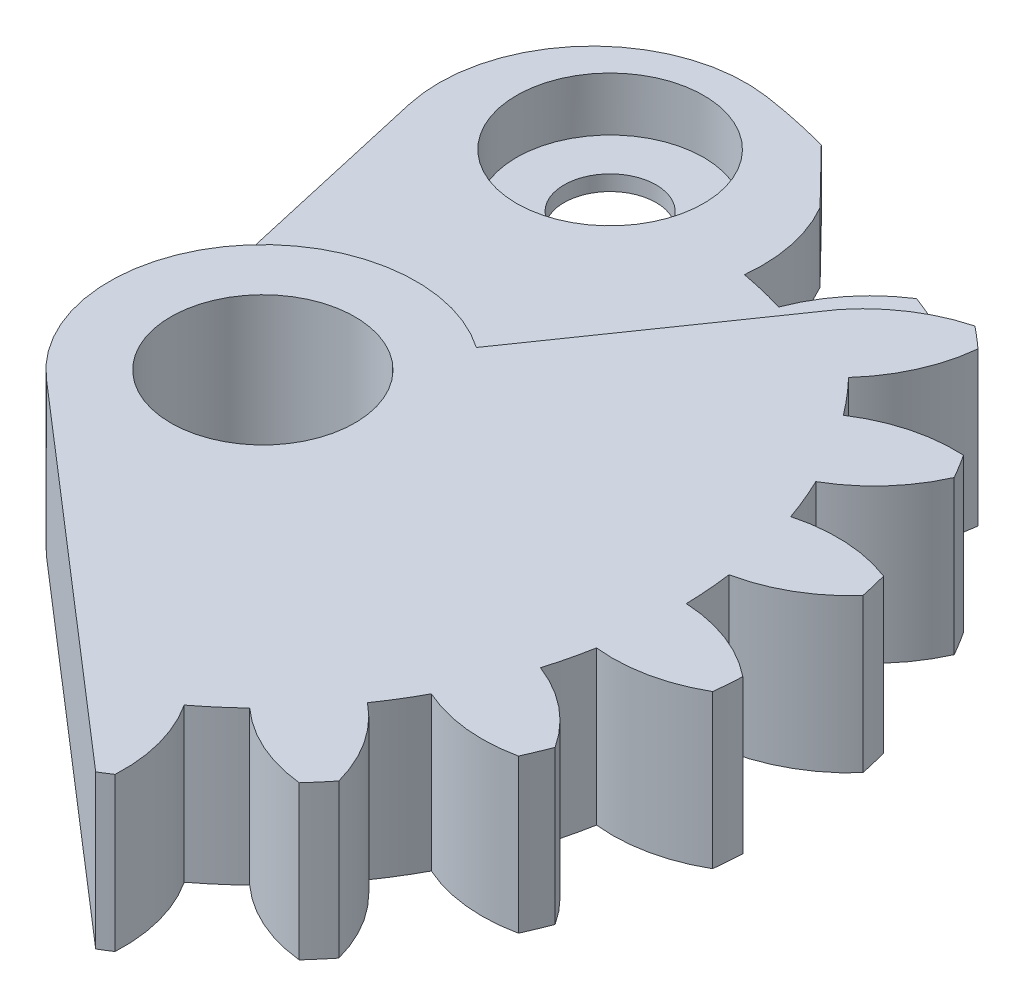
SolidWorks part; units mm, degrees
ref_plane "前视基准面" through (0, 0, 0) normal (0, 0, 1) x (1, 0, 0)
ref_plane "上视基准面" through (0, 0, 0) normal (0, 1, 0) x (1, 0, 0)
ref_plane "右视基准面" through (0, 0, 0) normal (1, 0, 0) x (0, 0, -1)
other "Configuration Table"
sketch "草图1" plane through (0, 0, 0) normal (0, 1, 0) x (1, 0, 0)
  line L0 (0, 0) -> (0, 56.9379) construction
  line L1 (0, 0) -> (19.4661, 53.4826) construction
  line L2 (0, 0) -> (4.4104, 56.0389) construction
  line L3 (0, 30) -> (9.6418, 26.4907) construction
  circle A0 centre (0, 0) radius 30 construction
  circle A1 centre (0, 0) radius 27
  circle A2 centre (0, 0) radius 33
  arc A3 (1.6756, 32.9574) -> (-0.6065, 26.9932) centre (9.6418, 26.4907) ccw
  arc A4 (3.5007, 32.8138) -> (4.8217, 26.566) centre (-5.3791, 27.6728) cw
  dimension "D1" = 60
  dimension "D2" = 3
  dimension "D3" = 3
  dimension "D4" = 20
  dimension "D5" = 4.5
extrude "凸台-拉伸2" add sketch "草图1" along normal blind 10 contours A1
sketch "草图3" plane through (0, 10, 0) normal (0, 1, 0) x (1, 0, 0)
  arc A0 (4.8217, 26.566) -> (3.5007, 32.8138) centre (-5.3791, 27.6728) ccw construction
  circle A1 centre (0, 0) radius 33
  circle A2 centre (0, 0) radius 33
  circle A3 centre (0, 0) radius 27
  circle A4 centre (0, 0) radius 27
  arc A5 (1.6756, 32.9574) -> (-0.6065, 26.9932) centre (9.6418, 26.4907) ccw construction
  arc A6 (4.8217, 26.566) -> (3.5007, 32.8138) centre (-5.3791, 27.6728) ccw
  arc A7 (1.6756, 32.9574) -> (-0.6065, 26.9932) centre (9.6418, 26.4907) ccw
  arc A8 (12.795, 23.7758) -> (13.4694, 30.126) centre (3.4356, 27.9806) ccw
  arc A9 (11.778, 30.8266) -> (7.7646, 25.8595) centre (17.356, 22.2146) ccw
  arc A10 (19.5159, 18.6582) -> (22.1196, 24.4892) centre (11.9139, 25.5495) ccw
  arc A11 (20.7275, 25.6782) -> (15.3755, 22.1944) centre (23.3712, 15.7641) ccw
  arc A12 (24.3264, 11.7143) -> (28.6046, 16.4553) centre (19.2261, 20.6174) ccw
  arc A13 (27.648, 18.0163) -> (21.4815, 16.3568) centre (27.0987, 7.7704) ccw
  arc A14 (26.7557, 3.6237) -> (32.2896, 6.8106) centre (24.6562, 13.6672) ccw
  arc A15 (31.8622, 8.5908) -> (25.4846, 8.9181) centre (28.1736, -0.9838) ccw
  arc A16 (26.566, -4.8217) -> (32.8138, -3.5007) centre (27.6728, 5.3791) ccw
  arc A17 (32.9574, -1.6756) -> (26.9932, 0.6065) centre (26.4907, -9.6418) ccw
  arc A18 (23.7758, -12.795) -> (30.126, -13.4694) centre (27.9806, -3.4356) ccw
  arc A19 (30.8266, -11.778) -> (25.8595, -7.7646) centre (22.2146, -17.356) ccw
  arc A20 (18.6582, -19.5159) -> (24.4892, -22.1196) centre (25.5495, -11.9139) ccw
  arc A21 (25.6782, -20.7275) -> (22.1944, -15.3755) centre (15.7641, -23.3712) ccw
  arc A22 (11.7143, -24.3264) -> (16.4553, -28.6046) centre (20.6174, -19.2261) ccw
  arc A23 (18.0163, -27.648) -> (16.3568, -21.4815) centre (7.7704, -27.0987) ccw
  arc A24 (3.6237, -26.7557) -> (6.8106, -32.2896) centre (13.6672, -24.6562) ccw
  arc A25 (8.5908, -31.8622) -> (8.9181, -25.4846) centre (-0.9838, -28.1736) ccw
  arc A26 (-4.8217, -26.566) -> (-3.5007, -32.8138) centre (5.3791, -27.6728) ccw
  arc A27 (-1.6756, -32.9574) -> (0.6065, -26.9932) centre (-9.6418, -26.4907) ccw
  arc A28 (-12.795, -23.7758) -> (-13.4694, -30.126) centre (-3.4356, -27.9806) ccw
  arc A29 (-11.778, -30.8266) -> (-7.7646, -25.8595) centre (-17.356, -22.2146) ccw
  arc A30 (-19.5159, -18.6582) -> (-22.1196, -24.4892) centre (-11.9139, -25.5495) ccw
  arc A31 (-20.7275, -25.6782) -> (-15.3755, -22.1944) centre (-23.3712, -15.7641) ccw
  arc A32 (-24.3264, -11.7143) -> (-28.6046, -16.4553) centre (-19.2261, -20.6174) ccw
  arc A33 (-27.648, -18.0163) -> (-21.4815, -16.3568) centre (-27.0987, -7.7704) ccw
  arc A34 (-26.7557, -3.6237) -> (-32.2896, -6.8106) centre (-24.6562, -13.6672) ccw
  arc A35 (-31.8622, -8.5908) -> (-25.4846, -8.9181) centre (-28.1736, 0.9838) ccw
  arc A36 (-26.566, 4.8217) -> (-32.8138, 3.5007) centre (-27.6728, -5.3791) ccw
  arc A37 (-32.9574, 1.6756) -> (-26.9932, -0.6065) centre (-26.4907, 9.6418) ccw
  arc A38 (-23.7758, 12.795) -> (-30.126, 13.4694) centre (-27.9806, 3.4356) ccw
  arc A39 (-30.8266, 11.778) -> (-25.8595, 7.7646) centre (-22.2146, 17.356) ccw
  arc A40 (-18.6582, 19.5159) -> (-24.4892, 22.1196) centre (-25.5495, 11.9139) ccw
  arc A41 (-25.6782, 20.7275) -> (-22.1944, 15.3755) centre (-15.7641, 23.3712) ccw
  arc A42 (-11.7143, 24.3264) -> (-16.4553, 28.6046) centre (-20.6174, 19.2261) ccw
  arc A43 (-18.0163, 27.648) -> (-16.3568, 21.4815) centre (-7.7704, 27.0987) ccw
  arc A44 (-3.6237, 26.7557) -> (-6.8106, 32.2896) centre (-13.6672, 24.6562) ccw
  arc A45 (-8.5908, 31.8622) -> (-8.9181, 25.4846) centre (0.9838, 28.1736) ccw
  point P129 (0, 0)
  circle M3 centre (0, 0) radius 27
  dimension "D1" = 0
  dimension "D2" = 0
  dimension "D3" = 20
extrude "凸台-拉伸3" add sketch "草图3" against normal blind 10 contours A2 A45 A44 M3 | A2 A43 A42 M3 | A2 A41 A40 M3 | A2 A39 A38 M3 | A2 A37 A36 M3 | A2 A35 A34 M3 | A2 A33 A32 M3 | A2 A31 A30 M3 | A2 A29 A28 M3 | A2 A27 A26 M3 | A2 A25 A24 M3 | A2 A23 A22 M3 | A2 A21 A20 M3 | A2 A19 A18 M3 | A2 A17 A16 M3 | A2 A15 A14 M3 | A2 A13 A12 M3 | A2 A11 A10 M3 | A2 A9 A8 M3 | A2 A7 A6 M3
sketch "草图4" plane through (0, 10, 0) normal (0, 1, 0) x (1, 0, 0)
  line L0 (0, 0) -> (23.0213, -14.1075)
  line L1 (0, 0) -> (-2.1184, 26.9168)
  line L2 (-9.5508, 2.9635) -> (19.9356, 97.9927)
  line L5 (-6.5422, -7.5631) -> (68.7094, -72.6568)
  arc A0 (16.4553, -28.6046) -> (18.0163, -27.648) centre (0, 0) ccw construction
  arc A1 (-0.6065, 26.9932) -> (-3.6237, 26.7557) centre (0, 0) ccw construction
  circle A2 centre (0, 0) radius 100
  arc A3 (22.1944, -15.3755) -> (23.7758, -12.795) centre (0, 0) ccw construction
  circle A4 centre (0, 0) radius 10
  point P9 (17.2425, -28.1371)
  point P18 (-2.1184, 26.9168)
  dimension "D1" = 20
  dimension "D2" = 200
extrude "切除-拉伸2" cut sketch "草图4" against normal through all
sketch "草图6" plane through (0, 10, 0) normal (0, 1, 0) x (1, 0, 0)
  line L2 (-6.5422, -7.5631) -> (17.2425, -28.1371)
  line L3 (-2.1184, 26.9168) -> (-9.5508, 2.9635)
  line L4 (-6.5422, -7.5631) -> (17.2425, -28.1371)
  line L5 (-2.1184, 26.9168) -> (-9.5508, 2.9635)
  circle A0 centre (0, 0) radius 6
  arc A22 (-9.5508, 2.9635) -> (-6.5422, -7.5631) centre (0, 0) ccw
  arc A23 (17.2425, -28.1371) -> (18.0163, -27.648) centre (0, 0) ccw
  arc A24 (30.8266, -11.778) -> (25.8595, -7.7646) centre (22.2146, -17.356) ccw
  arc A25 (25.8595, -7.7646) -> (26.566, -4.8217) centre (0, 0) ccw
  arc A26 (26.566, -4.8217) -> (32.8138, -3.5007) centre (27.6728, 5.3791) ccw
  arc A27 (32.8138, -3.5007) -> (32.9574, -1.6756) centre (0, 0) ccw
  arc A28 (32.9574, -1.6756) -> (26.9932, 0.6065) centre (26.4907, -9.6418) ccw
  arc A29 (26.9932, 0.6065) -> (26.7557, 3.6237) centre (0, 0) ccw
  arc A30 (26.7557, 3.6237) -> (32.2896, 6.8106) centre (24.6562, 13.6672) ccw
  arc A31 (32.2896, 6.8106) -> (31.8622, 8.5908) centre (0, 0) ccw
  arc A32 (31.8622, 8.5908) -> (25.4846, 8.9181) centre (28.1736, -0.9838) ccw
  arc A33 (25.4846, 8.9181) -> (24.3264, 11.7143) centre (0, 0) ccw
  arc A34 (24.3264, 11.7143) -> (28.6046, 16.4553) centre (19.2261, 20.6174) ccw
  arc A35 (28.6046, 16.4553) -> (27.648, 18.0163) centre (0, 0) ccw
  arc A36 (27.648, 18.0163) -> (21.4815, 16.3568) centre (27.0987, 7.7704) ccw
  arc A37 (21.4815, 16.3568) -> (19.5159, 18.6582) centre (0, 0) ccw
  arc A38 (19.5159, 18.6582) -> (22.1196, 24.4892) centre (11.9139, 25.5495) ccw
  arc A39 (22.1196, 24.4892) -> (20.7275, 25.6782) centre (0, 0) ccw
  arc A40 (20.7275, 25.6782) -> (15.3755, 22.1944) centre (23.3712, 15.7641) ccw
  arc A41 (15.3755, 22.1944) -> (12.795, 23.7758) centre (0, 0) ccw
  arc A42 (12.795, 23.7758) -> (13.4694, 30.126) centre (3.4356, 27.9806) ccw
  arc A43 (13.4694, 30.126) -> (11.778, 30.8266) centre (0, 0) ccw
  arc A44 (-9.5508, 2.9635) -> (-6.5422, -7.5631) centre (0, 0) ccw
  arc A45 (17.2425, -28.1371) -> (18.0163, -27.648) centre (0, 0) ccw
  arc A46 (30.8266, -11.778) -> (25.8595, -7.7646) centre (22.2146, -17.356) ccw
  arc A47 (25.8595, -7.7646) -> (26.566, -4.8217) centre (0, 0) ccw
  arc A48 (26.566, -4.8217) -> (32.8138, -3.5007) centre (27.6728, 5.3791) ccw
  arc A49 (32.8138, -3.5007) -> (32.9574, -1.6756) centre (0, 0) ccw
  arc A50 (32.9574, -1.6756) -> (26.9932, 0.6065) centre (26.4907, -9.6418) ccw
  arc A51 (26.9932, 0.6065) -> (26.7557, 3.6237) centre (0, 0) ccw
  arc A52 (26.7557, 3.6237) -> (32.2896, 6.8106) centre (24.6562, 13.6672) ccw
  arc A53 (32.2896, 6.8106) -> (31.8622, 8.5908) centre (0, 0) ccw
  arc A54 (31.8622, 8.5908) -> (25.4846, 8.9181) centre (28.1736, -0.9838) ccw
  arc A55 (25.4846, 8.9181) -> (24.3264, 11.7143) centre (0, 0) ccw
  arc A56 (24.3264, 11.7143) -> (28.6046, 16.4553) centre (19.2261, 20.6174) ccw
  arc A57 (28.6046, 16.4553) -> (27.648, 18.0163) centre (0, 0) ccw
  arc A58 (27.648, 18.0163) -> (21.4815, 16.3568) centre (27.0987, 7.7704) ccw
  arc A59 (21.4815, 16.3568) -> (19.5159, 18.6582) centre (0, 0) ccw
  arc A60 (19.5159, 18.6582) -> (22.1196, 24.4892) centre (11.9139, 25.5495) ccw
  arc A61 (22.1196, 24.4892) -> (20.7275, 25.6782) centre (0, 0) ccw
  arc A62 (20.7275, 25.6782) -> (15.3755, 22.1944) centre (23.3712, 15.7641) ccw
  arc A63 (15.3755, 22.1944) -> (12.795, 23.7758) centre (0, 0) ccw
  arc A64 (12.795, 23.7758) -> (13.4694, 30.126) centre (3.4356, 27.9806) ccw
  arc A65 (13.4694, 30.126) -> (11.778, 30.8266) centre (0, 0) ccw
  arc A73 (11.778, 30.8266) -> (7.7646, 25.8595) centre (17.356, 22.2146) ccw
  arc A74 (11.778, 30.8266) -> (7.7646, 25.8595) centre (17.356, 22.2146) ccw
  arc A75 (7.7646, 25.8595) -> (4.8217, 26.566) centre (0, 0) ccw
  arc A76 (7.7646, 25.8595) -> (4.8217, 26.566) centre (0, 0) ccw
  arc A77 (4.8217, 26.566) -> (3.5007, 32.8138) centre (-5.3791, 27.6728) ccw
  arc A78 (4.8217, 26.566) -> (3.5007, 32.8138) centre (-5.3791, 27.6728) ccw
  arc A79 (3.5007, 32.8138) -> (1.6756, 32.9574) centre (0, 0) ccw
  arc A80 (3.5007, 32.8138) -> (1.6756, 32.9574) centre (0, 0) ccw
  arc A81 (1.6756, 32.9574) -> (-0.6065, 26.9932) centre (9.6418, 26.4907) ccw
  arc A82 (1.6756, 32.9574) -> (-0.6065, 26.9932) centre (9.6418, 26.4907) ccw
  arc A83 (-0.6065, 26.9932) -> (-2.1184, 26.9168) centre (0, 0) ccw
  arc A84 (-0.6065, 26.9932) -> (-2.1184, 26.9168) centre (0, 0) ccw
  arc A89 (25.6782, -20.7275) -> (22.1944, -15.3755) centre (15.7641, -23.3712) ccw
  arc A90 (25.6782, -20.7275) -> (22.1944, -15.3755) centre (15.7641, -23.3712) ccw
  arc A91 (22.1944, -15.3755) -> (23.7758, -12.795) centre (0, 0) ccw
  arc A92 (22.1944, -15.3755) -> (23.7758, -12.795) centre (0, 0) ccw
  arc A93 (23.7758, -12.795) -> (30.126, -13.4694) centre (27.9806, -3.4356) ccw
  arc A94 (23.7758, -12.795) -> (30.126, -13.4694) centre (27.9806, -3.4356) ccw
  arc A95 (30.126, -13.4694) -> (30.8266, -11.778) centre (0, 0) ccw
  arc A96 (30.126, -13.4694) -> (30.8266, -11.778) centre (0, 0) ccw
  arc A101 (18.0163, -27.648) -> (16.3568, -21.4815) centre (7.7704, -27.0987) ccw
  arc A102 (18.0163, -27.648) -> (16.3568, -21.4815) centre (7.7704, -27.0987) ccw
  arc A103 (16.3568, -21.4815) -> (18.6582, -19.5159) centre (0, 0) ccw
  arc A104 (16.3568, -21.4815) -> (18.6582, -19.5159) centre (0, 0) ccw
  arc A105 (18.6582, -19.5159) -> (24.4892, -22.1196) centre (25.5495, -11.9139) ccw
  arc A106 (18.6582, -19.5159) -> (24.4892, -22.1196) centre (25.5495, -11.9139) ccw
  arc A107 (24.4892, -22.1196) -> (25.6782, -20.7275) centre (0, 0) ccw
  arc A108 (24.4892, -22.1196) -> (25.6782, -20.7275) centre (0, 0) ccw
  dimension "D2" = 12
  dimension "D1" = 0
extrude "切除-拉伸3" cut sketch "草图6" against normal blind 10 contours A0
sketch "草图9" plane through (0, 10, 0) normal (0, 1, 0) x (1, 0, 0)
  line L0 (-10, 0) -> (-18.3373, 36.811)
  line L1 (-6.5422, -7.5631) -> (4.8217, 26.566)
  line L2 (4.8217, 26.566) -> (7.168, 33.6128)
  line L3 (-6.5422, -7.5631) -> (17.2425, -28.1371)
  line L4 (-2.1184, 26.9168) -> (-9.5508, 2.9635)
  line L5 (-6.5422, -7.5631) -> (17.2425, -28.1371)
  line L6 (-2.1184, 26.9168) -> (-9.5508, 2.9635)
  arc A0 (-9.5508, 2.9635) -> (-6.5422, -7.5631) centre (0, 0) ccw construction
  circle A1 centre (-10, 0) radius 37.7433
  arc A42 (-9.5508, 2.9635) -> (-6.5422, -7.5631) centre (0, 0) ccw
  arc A43 (17.2425, -28.1371) -> (18.0163, -27.648) centre (0, 0) ccw
  arc A48 (18.0163, -27.648) -> (16.3568, -21.4815) centre (7.7704, -27.0987) ccw
  arc A49 (16.3568, -21.4815) -> (18.6582, -19.5159) centre (0, 0) ccw
  arc A50 (18.6582, -19.5159) -> (24.4892, -22.1196) centre (25.5495, -11.9139) ccw
  arc A51 (24.4892, -22.1196) -> (25.6782, -20.7275) centre (0, 0) ccw
  arc A52 (25.6782, -20.7275) -> (22.1944, -15.3755) centre (15.7641, -23.3712) ccw
  arc A53 (22.1944, -15.3755) -> (23.7758, -12.795) centre (0, 0) ccw
  arc A54 (23.7758, -12.795) -> (30.126, -13.4694) centre (27.9806, -3.4356) ccw
  arc A55 (30.126, -13.4694) -> (30.8266, -11.778) centre (0, 0) ccw
  arc A56 (30.8266, -11.778) -> (25.8595, -7.7646) centre (22.2146, -17.356) ccw
  arc A57 (25.8595, -7.7646) -> (26.566, -4.8217) centre (0, 0) ccw
  arc A58 (26.566, -4.8217) -> (32.8138, -3.5007) centre (27.6728, 5.3791) ccw
  arc A59 (32.8138, -3.5007) -> (32.9574, -1.6756) centre (0, 0) ccw
  arc A60 (32.9574, -1.6756) -> (26.9932, 0.6065) centre (26.4907, -9.6418) ccw
  arc A61 (26.9932, 0.6065) -> (26.7557, 3.6237) centre (0, 0) ccw
  arc A62 (26.7557, 3.6237) -> (32.2896, 6.8106) centre (24.6562, 13.6672) ccw
  arc A63 (32.2896, 6.8106) -> (31.8622, 8.5908) centre (0, 0) ccw
  arc A64 (31.8622, 8.5908) -> (25.4846, 8.9181) centre (28.1736, -0.9838) ccw
  arc A65 (25.4846, 8.9181) -> (24.3264, 11.7143) centre (0, 0) ccw
  arc A66 (24.3264, 11.7143) -> (28.6046, 16.4553) centre (19.2261, 20.6174) ccw
  arc A67 (28.6046, 16.4553) -> (27.648, 18.0163) centre (0, 0) ccw
  arc A68 (27.648, 18.0163) -> (21.4815, 16.3568) centre (27.0987, 7.7704) ccw
  arc A69 (21.4815, 16.3568) -> (19.5159, 18.6582) centre (0, 0) ccw
  arc A70 (19.5159, 18.6582) -> (22.1196, 24.4892) centre (11.9139, 25.5495) ccw
  arc A71 (22.1196, 24.4892) -> (20.7275, 25.6782) centre (0, 0) ccw
  arc A72 (20.7275, 25.6782) -> (15.3755, 22.1944) centre (23.3712, 15.7641) ccw
  arc A73 (15.3755, 22.1944) -> (12.795, 23.7758) centre (0, 0) ccw
  arc A74 (12.795, 23.7758) -> (13.4694, 30.126) centre (3.4356, 27.9806) ccw
  arc A75 (13.4694, 30.126) -> (11.778, 30.8266) centre (0, 0) ccw
  arc A76 (11.778, 30.8266) -> (7.7646, 25.8595) centre (17.356, 22.2146) ccw
  arc A77 (7.7646, 25.8595) -> (4.8217, 26.566) centre (0, 0) ccw
  arc A78 (4.8217, 26.566) -> (3.5007, 32.8138) centre (-5.3791, 27.6728) ccw
  arc A79 (3.5007, 32.8138) -> (1.6756, 32.9574) centre (0, 0) ccw
  arc A80 (1.6756, 32.9574) -> (-0.6065, 26.9932) centre (9.6418, 26.4907) ccw
  arc A81 (-0.6065, 26.9932) -> (-2.1184, 26.9168) centre (0, 0) ccw
  arc A82 (-9.5508, 2.9635) -> (-6.5422, -7.5631) centre (0, 0) ccw
  arc A83 (17.2425, -28.1371) -> (18.0163, -27.648) centre (0, 0) ccw
  arc A88 (18.0163, -27.648) -> (16.3568, -21.4815) centre (7.7704, -27.0987) ccw
  arc A89 (16.3568, -21.4815) -> (18.6582, -19.5159) centre (0, 0) ccw
  arc A90 (18.6582, -19.5159) -> (24.4892, -22.1196) centre (25.5495, -11.9139) ccw
  arc A91 (24.4892, -22.1196) -> (25.6782, -20.7275) centre (0, 0) ccw
  arc A92 (25.6782, -20.7275) -> (22.1944, -15.3755) centre (15.7641, -23.3712) ccw
  arc A93 (22.1944, -15.3755) -> (23.7758, -12.795) centre (0, 0) ccw
  arc A94 (23.7758, -12.795) -> (30.126, -13.4694) centre (27.9806, -3.4356) ccw
  arc A95 (30.126, -13.4694) -> (30.8266, -11.778) centre (0, 0) ccw
  arc A96 (30.8266, -11.778) -> (25.8595, -7.7646) centre (22.2146, -17.356) ccw
  arc A97 (25.8595, -7.7646) -> (26.566, -4.8217) centre (0, 0) ccw
  arc A98 (26.566, -4.8217) -> (32.8138, -3.5007) centre (27.6728, 5.3791) ccw
  arc A99 (32.8138, -3.5007) -> (32.9574, -1.6756) centre (0, 0) ccw
  arc A100 (32.9574, -1.6756) -> (26.9932, 0.6065) centre (26.4907, -9.6418) ccw
  arc A101 (26.9932, 0.6065) -> (26.7557, 3.6237) centre (0, 0) ccw
  arc A102 (26.7557, 3.6237) -> (32.2896, 6.8106) centre (24.6562, 13.6672) ccw
  arc A103 (32.2896, 6.8106) -> (31.8622, 8.5908) centre (0, 0) ccw
  arc A104 (31.8622, 8.5908) -> (25.4846, 8.9181) centre (28.1736, -0.9838) ccw
  arc A105 (25.4846, 8.9181) -> (24.3264, 11.7143) centre (0, 0) ccw
  arc A106 (24.3264, 11.7143) -> (28.6046, 16.4553) centre (19.2261, 20.6174) ccw
  arc A107 (28.6046, 16.4553) -> (27.648, 18.0163) centre (0, 0) ccw
  arc A108 (27.648, 18.0163) -> (21.4815, 16.3568) centre (27.0987, 7.7704) ccw
  arc A109 (21.4815, 16.3568) -> (19.5159, 18.6582) centre (0, 0) ccw
  arc A110 (19.5159, 18.6582) -> (22.1196, 24.4892) centre (11.9139, 25.5495) ccw
  arc A111 (22.1196, 24.4892) -> (20.7275, 25.6782) centre (0, 0) ccw
  arc A112 (20.7275, 25.6782) -> (15.3755, 22.1944) centre (23.3712, 15.7641) ccw
  arc A113 (15.3755, 22.1944) -> (12.795, 23.7758) centre (0, 0) ccw
  arc A114 (12.795, 23.7758) -> (13.4694, 30.126) centre (3.4356, 27.9806) ccw
  arc A115 (13.4694, 30.126) -> (11.778, 30.8266) centre (0, 0) ccw
  arc A116 (11.778, 30.8266) -> (7.7646, 25.8595) centre (17.356, 22.2146) ccw
  arc A117 (7.7646, 25.8595) -> (4.8217, 26.566) centre (0, 0) ccw
  arc A118 (4.8217, 26.566) -> (3.5007, 32.8138) centre (-5.3791, 27.6728) ccw
  arc A119 (3.5007, 32.8138) -> (1.6756, 32.9574) centre (0, 0) ccw
  arc A120 (1.6756, 32.9574) -> (-0.6065, 26.9932) centre (9.6418, 26.4907) ccw
  arc A121 (-0.6065, 26.9932) -> (-2.1184, 26.9168) centre (0, 0) ccw
  arc M46 (-9.5508, 2.9635) -> (-6.5422, -7.5631) centre (0, 0) ccw
  arc M81 (11.778, 30.8266) -> (7.7646, 25.8595) centre (17.356, 22.2146) ccw
  arc M82 (7.7646, 25.8595) -> (4.8217, 26.566) centre (0, 0) ccw
  arc M83 (4.8217, 26.566) -> (3.5007, 32.8138) centre (-5.3791, 27.6728) ccw
  arc M84 (3.5007, 32.8138) -> (1.6756, 32.9574) centre (0, 0) ccw
  arc M85 (1.6756, 32.9574) -> (-0.6065, 26.9932) centre (9.6418, 26.4907) ccw
  arc M86 (-0.6065, 26.9932) -> (-2.1184, 26.9168) centre (0, 0) ccw
  line M87 (-2.1184, 26.9168) -> (-9.5508, 2.9635)
  dimension "D1" = 0
  dimension "D2" = 30
extrude "凸台-拉伸5" add sketch "草图9" against normal blind 10 contours A1 L0 M81 M46 M87 M86 M85 M84 M83 M82
sketch "草图10" plane through (0, 10, 0) normal (0, 1, 0) x (1, 0, 0)
  line L0 (-6.6268, 29.2589) -> (0, 0)
  line L1 (-10, 0) -> (-18.3373, 36.811) construction
  circle A0 centre (-6.6268, 29.2589) radius 6.1
  dimension "D1" = 12.2
  dimension "D2" = 30
extrude "切除-拉伸5" cut sketch "草图10" against normal blind 10
sketch "草图11" plane through (0, 10, 0) normal (0, 1, 0) x (1, 0, 0)
  line L0 (3.5007, 32.8138) -> (0, 36.3945)
  line L1 (0, 0) -> (0, 56.9379) construction
  line L5 (-18.3373, 36.811) -> (-10, 0)
  line L6 (-6.5422, -7.5631) -> (17.2425, -28.1371)
  line L7 (4.8217, 26.566) -> (7.168, 33.6128)
  line L8 (-18.3373, 36.811) -> (-10, 0)
  line L9 (-6.5422, -7.5631) -> (17.2425, -28.1371)
  line L10 (4.8217, 26.566) -> (7.168, 33.6128)
  arc A0 (4.8217, 26.566) -> (3.5007, 32.8138) centre (-5.3791, 27.6728) ccw construction
  arc A1 (4.8217, 26.566) -> (3.5007, 32.8138) centre (-5.3791, 27.6728) ccw
  arc A2 (7.168, 33.6128) -> (-18.3373, 36.811) centre (-10, 0) ccw construction
  arc A40 (-10, 0) -> (-6.5422, -7.5631) centre (0, 0) ccw
  arc A41 (17.2425, -28.1371) -> (18.0163, -27.648) centre (0, 0) ccw
  arc A46 (18.0163, -27.648) -> (16.3568, -21.4815) centre (7.7704, -27.0987) ccw
  arc A47 (16.3568, -21.4815) -> (18.6582, -19.5159) centre (0, 0) ccw
  arc A48 (18.6582, -19.5159) -> (24.4892, -22.1196) centre (25.5495, -11.9139) ccw
  arc A49 (24.4892, -22.1196) -> (25.6782, -20.7275) centre (0, 0) ccw
  arc A50 (25.6782, -20.7275) -> (22.1944, -15.3755) centre (15.7641, -23.3712) ccw
  arc A51 (22.1944, -15.3755) -> (23.7758, -12.795) centre (0, 0) ccw
  arc A52 (23.7758, -12.795) -> (30.126, -13.4694) centre (27.9806, -3.4356) ccw
  arc A53 (30.126, -13.4694) -> (30.8266, -11.778) centre (0, 0) ccw
  arc A54 (30.8266, -11.778) -> (25.8595, -7.7646) centre (22.2146, -17.356) ccw
  arc A55 (25.8595, -7.7646) -> (26.566, -4.8217) centre (0, 0) ccw
  arc A56 (26.566, -4.8217) -> (32.8138, -3.5007) centre (27.6728, 5.3791) ccw
  arc A57 (32.8138, -3.5007) -> (32.9574, -1.6756) centre (0, 0) ccw
  arc A58 (32.9574, -1.6756) -> (26.9932, 0.6065) centre (26.4907, -9.6418) ccw
  arc A59 (26.9932, 0.6065) -> (26.7557, 3.6237) centre (0, 0) ccw
  arc A60 (26.7557, 3.6237) -> (32.2896, 6.8106) centre (24.6562, 13.6672) ccw
  arc A61 (32.2896, 6.8106) -> (31.8622, 8.5908) centre (0, 0) ccw
  arc A62 (31.8622, 8.5908) -> (25.4846, 8.9181) centre (28.1736, -0.9838) ccw
  arc A63 (25.4846, 8.9181) -> (24.3264, 11.7143) centre (0, 0) ccw
  arc A64 (24.3264, 11.7143) -> (28.6046, 16.4553) centre (19.2261, 20.6174) ccw
  arc A65 (28.6046, 16.4553) -> (27.648, 18.0163) centre (0, 0) ccw
  arc A66 (27.648, 18.0163) -> (21.4815, 16.3568) centre (27.0987, 7.7704) ccw
  arc A67 (21.4815, 16.3568) -> (19.5159, 18.6582) centre (0, 0) ccw
  arc A68 (19.5159, 18.6582) -> (22.1196, 24.4892) centre (11.9139, 25.5495) ccw
  arc A69 (22.1196, 24.4892) -> (20.7275, 25.6782) centre (0, 0) ccw
  arc A70 (20.7275, 25.6782) -> (15.3755, 22.1944) centre (23.3712, 15.7641) ccw
  arc A71 (15.3755, 22.1944) -> (12.795, 23.7758) centre (0, 0) ccw
  arc A72 (12.795, 23.7758) -> (13.4694, 30.126) centre (3.4356, 27.9806) ccw
  arc A73 (13.4694, 30.126) -> (11.778, 30.8266) centre (0, 0) ccw
  arc A74 (11.778, 30.8266) -> (7.7646, 25.8595) centre (17.356, 22.2146) ccw
  arc A75 (7.7646, 25.8595) -> (4.8217, 26.566) centre (0, 0) ccw
  arc A76 (7.168, 33.6128) -> (-18.3373, 36.811) centre (-10, 0) ccw
  arc A77 (-10, 0) -> (-6.5422, -7.5631) centre (0, 0) ccw
  arc A78 (17.2425, -28.1371) -> (18.0163, -27.648) centre (0, 0) ccw
  arc A83 (18.0163, -27.648) -> (16.3568, -21.4815) centre (7.7704, -27.0987) ccw
  arc A84 (16.3568, -21.4815) -> (18.6582, -19.5159) centre (0, 0) ccw
  arc A85 (18.6582, -19.5159) -> (24.4892, -22.1196) centre (25.5495, -11.9139) ccw
  arc A86 (24.4892, -22.1196) -> (25.6782, -20.7275) centre (0, 0) ccw
  arc A87 (25.6782, -20.7275) -> (22.1944, -15.3755) centre (15.7641, -23.3712) ccw
  arc A88 (22.1944, -15.3755) -> (23.7758, -12.795) centre (0, 0) ccw
  arc A89 (23.7758, -12.795) -> (30.126, -13.4694) centre (27.9806, -3.4356) ccw
  arc A90 (30.126, -13.4694) -> (30.8266, -11.778) centre (0, 0) ccw
  arc A91 (30.8266, -11.778) -> (25.8595, -7.7646) centre (22.2146, -17.356) ccw
  arc A92 (25.8595, -7.7646) -> (26.566, -4.8217) centre (0, 0) ccw
  arc A93 (26.566, -4.8217) -> (32.8138, -3.5007) centre (27.6728, 5.3791) ccw
  arc A94 (32.8138, -3.5007) -> (32.9574, -1.6756) centre (0, 0) ccw
  arc A95 (32.9574, -1.6756) -> (26.9932, 0.6065) centre (26.4907, -9.6418) ccw
  arc A96 (26.9932, 0.6065) -> (26.7557, 3.6237) centre (0, 0) ccw
  arc A97 (26.7557, 3.6237) -> (32.2896, 6.8106) centre (24.6562, 13.6672) ccw
  arc A98 (32.2896, 6.8106) -> (31.8622, 8.5908) centre (0, 0) ccw
  arc A99 (31.8622, 8.5908) -> (25.4846, 8.9181) centre (28.1736, -0.9838) ccw
  arc A100 (25.4846, 8.9181) -> (24.3264, 11.7143) centre (0, 0) ccw
  arc A101 (24.3264, 11.7143) -> (28.6046, 16.4553) centre (19.2261, 20.6174) ccw
  arc A102 (28.6046, 16.4553) -> (27.648, 18.0163) centre (0, 0) ccw
  arc A103 (27.648, 18.0163) -> (21.4815, 16.3568) centre (27.0987, 7.7704) ccw
  arc A104 (21.4815, 16.3568) -> (19.5159, 18.6582) centre (0, 0) ccw
  arc A105 (19.5159, 18.6582) -> (22.1196, 24.4892) centre (11.9139, 25.5495) ccw
  arc A106 (22.1196, 24.4892) -> (20.7275, 25.6782) centre (0, 0) ccw
  arc A107 (20.7275, 25.6782) -> (15.3755, 22.1944) centre (23.3712, 15.7641) ccw
  arc A108 (15.3755, 22.1944) -> (12.795, 23.7758) centre (0, 0) ccw
  arc A109 (12.795, 23.7758) -> (13.4694, 30.126) centre (3.4356, 27.9806) ccw
  arc A110 (13.4694, 30.126) -> (11.778, 30.8266) centre (0, 0) ccw
  arc A111 (11.778, 30.8266) -> (7.7646, 25.8595) centre (17.356, 22.2146) ccw
  arc A112 (7.7646, 25.8595) -> (4.8217, 26.566) centre (0, 0) ccw
  arc A113 (7.168, 33.6128) -> (-18.3373, 36.811) centre (-10, 0) ccw
  line M80 (4.8217, 26.566) -> (7.168, 33.6128)
  arc M81 (7.168, 33.6128) -> (-18.3373, 36.811) centre (-10, 0) ccw
  dimension "D1" = 0
extrude "切除-拉伸6" cut sketch "草图11" against normal blind 10 contours A1 L0 M80 M81
fillet "圆角1" radius 10 1 edges at (-18.3373, 5, -36.811)
sketch "草图12" plane through (0, 10, 0) normal (0, 1, 0) x (1, 0, 0)
  circle A0 centre (0, 0) radius 6
  circle A1 centre (0, 0) radius 6 construction
  circle A2 centre (0, 0) radius 10
  arc A3 (-10, 0) -> (-6.5422, -7.5631) centre (0, 0) ccw construction
sketch "草图13" plane through (0, 0, 0) normal (0, -1, 0) x (1, 0, 0)
  line L2 (17.2425, 28.1371) -> (-6.5422, 7.5631)
  line L3 (17.2425, 28.1371) -> (-6.5422, 7.5631)
  line L4 (-10, 0) -> (-15.7164, -25.2392)
  line L10 (-10, 0) -> (-15.7164, -25.2392)
  line L11 (0, -36.3945) -> (3.5007, -32.8138)
  line L12 (0, -36.3945) -> (3.5007, -32.8138)
  arc A0 (-4.5084, -37.3417) -> (-15.7164, -25.2392) centre (-5.9634, -27.4481) ccw construction
  circle A1 centre (-6.6268, -29.2589) radius 6.1 construction
  arc A2 (-4.5084, -37.3417) -> (-15.7164, -25.2392) centre (-5.9634, -27.4481) ccw
  circle A3 centre (-6.6268, -29.2589) radius 6.1
  circle A4 centre (-6.6268, -29.2589) radius 8.0715
  arc A7 (-6.5422, 7.5631) -> (-10, 0) centre (0, 0) ccw
  arc A8 (-6.5422, 7.5631) -> (-10, 0) centre (0, 0) ccw
  arc A41 (-15.7164, -25.2392) -> (-4.5084, -37.3417) centre (-5.9634, -27.4481) ccw
  arc A42 (4.8217, -26.566) -> (7.7646, -25.8595) centre (0, 0) ccw
  arc A43 (-15.7164, -25.2392) -> (-4.5084, -37.3417) centre (-5.9634, -27.4481) ccw
  arc A44 (-4.5084, -37.3417) -> (0, -36.3945) centre (-10, 0) ccw
  arc A46 (7.7646, -25.8595) -> (11.778, -30.8266) centre (17.356, -22.2146) ccw
  arc A47 (7.7646, -25.8595) -> (11.778, -30.8266) centre (17.356, -22.2146) ccw
  arc A48 (11.778, -30.8266) -> (13.4694, -30.126) centre (0, 0) ccw
  arc A49 (11.778, -30.8266) -> (13.4694, -30.126) centre (0, 0) ccw
  arc A50 (13.4694, -30.126) -> (12.795, -23.7758) centre (3.4356, -27.9806) ccw
  arc A51 (13.4694, -30.126) -> (12.795, -23.7758) centre (3.4356, -27.9806) ccw
  arc A52 (12.795, -23.7758) -> (15.3755, -22.1944) centre (0, 0) ccw
  arc A53 (12.795, -23.7758) -> (15.3755, -22.1944) centre (0, 0) ccw
  arc A54 (15.3755, -22.1944) -> (20.7275, -25.6782) centre (23.3712, -15.7641) ccw
  arc A55 (15.3755, -22.1944) -> (20.7275, -25.6782) centre (23.3712, -15.7641) ccw
  arc A56 (20.7275, -25.6782) -> (22.1196, -24.4892) centre (0, 0) ccw
  arc A57 (20.7275, -25.6782) -> (22.1196, -24.4892) centre (0, 0) ccw
  arc A58 (22.1196, -24.4892) -> (19.5159, -18.6582) centre (11.9139, -25.5495) ccw
  arc A59 (22.1196, -24.4892) -> (19.5159, -18.6582) centre (11.9139, -25.5495) ccw
  arc A60 (19.5159, -18.6582) -> (21.4815, -16.3568) centre (0, 0) ccw
  arc A61 (19.5159, -18.6582) -> (21.4815, -16.3568) centre (0, 0) ccw
  arc A62 (21.4815, -16.3568) -> (27.648, -18.0163) centre (27.0987, -7.7704) ccw
  arc A63 (21.4815, -16.3568) -> (27.648, -18.0163) centre (27.0987, -7.7704) ccw
  arc A64 (27.648, -18.0163) -> (28.6046, -16.4553) centre (0, 0) ccw
  arc A65 (27.648, -18.0163) -> (28.6046, -16.4553) centre (0, 0) ccw
  arc A66 (28.6046, -16.4553) -> (24.3264, -11.7143) centre (19.2261, -20.6174) ccw
  arc A67 (28.6046, -16.4553) -> (24.3264, -11.7143) centre (19.2261, -20.6174) ccw
  arc A68 (24.3264, -11.7143) -> (25.4846, -8.9181) centre (0, 0) ccw
  arc A69 (24.3264, -11.7143) -> (25.4846, -8.9181) centre (0, 0) ccw
  arc A70 (25.4846, -8.9181) -> (31.8622, -8.5908) centre (28.1736, 0.9838) ccw
  arc A71 (25.4846, -8.9181) -> (31.8622, -8.5908) centre (28.1736, 0.9838) ccw
  arc A72 (31.8622, -8.5908) -> (32.2896, -6.8106) centre (0, 0) ccw
  arc A73 (31.8622, -8.5908) -> (32.2896, -6.8106) centre (0, 0) ccw
  arc A77 (4.8217, -26.566) -> (7.7646, -25.8595) centre (0, 0) ccw
  arc A109 (32.2896, -6.8106) -> (26.7557, -3.6237) centre (24.6562, -13.6672) ccw
  arc A110 (32.2896, -6.8106) -> (26.7557, -3.6237) centre (24.6562, -13.6672) ccw
  arc A111 (26.7557, -3.6237) -> (26.9932, -0.6065) centre (0, 0) ccw
  arc A112 (26.7557, -3.6237) -> (26.9932, -0.6065) centre (0, 0) ccw
  arc A113 (26.9932, -0.6065) -> (32.9574, 1.6756) centre (26.4907, 9.6418) ccw
  arc A114 (26.9932, -0.6065) -> (32.9574, 1.6756) centre (26.4907, 9.6418) ccw
  arc A115 (32.9574, 1.6756) -> (32.8138, 3.5007) centre (0, 0) ccw
  arc A116 (32.9574, 1.6756) -> (32.8138, 3.5007) centre (0, 0) ccw
  arc A117 (32.8138, 3.5007) -> (26.566, 4.8217) centre (27.6728, -5.3791) ccw
  arc A118 (32.8138, 3.5007) -> (26.566, 4.8217) centre (27.6728, -5.3791) ccw
  arc A119 (26.566, 4.8217) -> (25.8595, 7.7646) centre (0, 0) ccw
  arc A120 (26.566, 4.8217) -> (25.8595, 7.7646) centre (0, 0) ccw
  arc A121 (25.8595, 7.7646) -> (30.8266, 11.778) centre (22.2146, 17.356) ccw
  arc A122 (25.8595, 7.7646) -> (30.8266, 11.778) centre (22.2146, 17.356) ccw
  arc A123 (30.8266, 11.778) -> (30.126, 13.4694) centre (0, 0) ccw
  arc A124 (30.8266, 11.778) -> (30.126, 13.4694) centre (0, 0) ccw
  arc A125 (30.126, 13.4694) -> (23.7758, 12.795) centre (27.9806, 3.4356) ccw
  arc A126 (30.126, 13.4694) -> (23.7758, 12.795) centre (27.9806, 3.4356) ccw
  arc A127 (23.7758, 12.795) -> (22.1944, 15.3755) centre (0, 0) ccw
  arc A128 (23.7758, 12.795) -> (22.1944, 15.3755) centre (0, 0) ccw
  arc A129 (22.1944, 15.3755) -> (25.6782, 20.7275) centre (15.7641, 23.3712) ccw
  arc A130 (22.1944, 15.3755) -> (25.6782, 20.7275) centre (15.7641, 23.3712) ccw
  arc A131 (25.6782, 20.7275) -> (24.4892, 22.1196) centre (0, 0) ccw
  arc A132 (25.6782, 20.7275) -> (24.4892, 22.1196) centre (0, 0) ccw
  arc A133 (24.4892, 22.1196) -> (18.6582, 19.5159) centre (25.5495, 11.9139) ccw
  arc A134 (24.4892, 22.1196) -> (18.6582, 19.5159) centre (25.5495, 11.9139) ccw
  arc A135 (18.6582, 19.5159) -> (16.3568, 21.4815) centre (0, 0) ccw
  arc A136 (18.6582, 19.5159) -> (16.3568, 21.4815) centre (0, 0) ccw
  arc A137 (16.3568, 21.4815) -> (18.0163, 27.648) centre (7.7704, 27.0987) ccw
  arc A138 (16.3568, 21.4815) -> (18.0163, 27.648) centre (7.7704, 27.0987) ccw
  arc A139 (18.0163, 27.648) -> (17.2425, 28.1371) centre (0, 0) ccw
  arc A140 (18.0163, 27.648) -> (17.2425, 28.1371) centre (0, 0) ccw
  arc A141 (-4.5084, -37.3417) -> (0, -36.3945) centre (-10, 0) ccw
  arc A145 (3.5007, -32.8138) -> (4.8217, -26.566) centre (-5.3791, -27.6728) ccw
  arc A147 (3.5007, -32.8138) -> (4.8217, -26.566) centre (-5.3791, -27.6728) ccw
  dimension "D1" = 0
sketch "草图14" plane through (0, 10, 0) normal (0, 1, 0) x (1, 0, 0)
  line L0 (15.3755, 22.1944) -> (0, 0)
  line L3 (-15.7164, 25.2392) -> (-10, 0)
  line L4 (-6.5422, -7.5631) -> (17.2425, -28.1371)
  line L5 (3.5007, 32.8138) -> (0, 36.3945)
  line L6 (-15.7164, 25.2392) -> (-10, 0)
  line L7 (-6.5422, -7.5631) -> (17.2425, -28.1371)
  line L8 (3.5007, 32.8138) -> (0, 36.3945)
  circle A0 centre (0, 0) radius 10
  circle A1 centre (0, 0) radius 6
  circle A2 centre (0, 0) radius 6
  circle A3 centre (-6.6268, 29.2589) radius 6.1
  circle A4 centre (-6.6268, 29.2589) radius 6.1
  arc A39 (0, 36.3945) -> (-4.5084, 37.3417) centre (-10, 0) ccw
  arc A40 (-4.5084, 37.3417) -> (-15.7164, 25.2392) centre (-5.9634, 27.4481) ccw
  arc A41 (-10, 0) -> (-6.5422, -7.5631) centre (0, 0) ccw
  arc A42 (17.2425, -28.1371) -> (18.0163, -27.648) centre (0, 0) ccw
  arc A43 (18.0163, -27.648) -> (16.3568, -21.4815) centre (7.7704, -27.0987) ccw
  arc A44 (16.3568, -21.4815) -> (18.6582, -19.5159) centre (0, 0) ccw
  arc A45 (18.6582, -19.5159) -> (24.4892, -22.1196) centre (25.5495, -11.9139) ccw
  arc A46 (24.4892, -22.1196) -> (25.6782, -20.7275) centre (0, 0) ccw
  arc A47 (25.6782, -20.7275) -> (22.1944, -15.3755) centre (15.7641, -23.3712) ccw
  arc A48 (22.1944, -15.3755) -> (23.7758, -12.795) centre (0, 0) ccw
  arc A49 (23.7758, -12.795) -> (30.126, -13.4694) centre (27.9806, -3.4356) ccw
  arc A50 (30.126, -13.4694) -> (30.8266, -11.778) centre (0, 0) ccw
  arc A51 (30.8266, -11.778) -> (25.8595, -7.7646) centre (22.2146, -17.356) ccw
  arc A52 (25.8595, -7.7646) -> (26.566, -4.8217) centre (0, 0) ccw
  arc A53 (26.566, -4.8217) -> (32.8138, -3.5007) centre (27.6728, 5.3791) ccw
  arc A54 (32.8138, -3.5007) -> (32.9574, -1.6756) centre (0, 0) ccw
  arc A55 (32.9574, -1.6756) -> (26.9932, 0.6065) centre (26.4907, -9.6418) ccw
  arc A56 (26.9932, 0.6065) -> (26.7557, 3.6237) centre (0, 0) ccw
  arc A57 (26.7557, 3.6237) -> (32.2896, 6.8106) centre (24.6562, 13.6672) ccw
  arc A58 (32.2896, 6.8106) -> (31.8622, 8.5908) centre (0, 0) ccw
  arc A59 (31.8622, 8.5908) -> (25.4846, 8.9181) centre (28.1736, -0.9838) ccw
  arc A60 (25.4846, 8.9181) -> (24.3264, 11.7143) centre (0, 0) ccw
  arc A61 (24.3264, 11.7143) -> (28.6046, 16.4553) centre (19.2261, 20.6174) ccw
  arc A62 (28.6046, 16.4553) -> (27.648, 18.0163) centre (0, 0) ccw
  arc A63 (27.648, 18.0163) -> (21.4815, 16.3568) centre (27.0987, 7.7704) ccw
  arc A64 (21.4815, 16.3568) -> (19.5159, 18.6582) centre (0, 0) ccw
  arc A65 (19.5159, 18.6582) -> (22.1196, 24.4892) centre (11.9139, 25.5495) ccw
  arc A66 (22.1196, 24.4892) -> (20.7275, 25.6782) centre (0, 0) ccw
  arc A67 (20.7275, 25.6782) -> (15.3755, 22.1944) centre (23.3712, 15.7641) ccw
  arc A68 (15.3755, 22.1944) -> (12.795, 23.7758) centre (0, 0) ccw
  arc A69 (12.795, 23.7758) -> (13.4694, 30.126) centre (3.4356, 27.9806) ccw
  arc A70 (13.4694, 30.126) -> (11.778, 30.8266) centre (0, 0) ccw
  arc A71 (11.778, 30.8266) -> (7.7646, 25.8595) centre (17.356, 22.2146) ccw
  arc A72 (7.7646, 25.8595) -> (4.8217, 26.566) centre (0, 0) ccw
  arc A73 (4.8217, 26.566) -> (3.5007, 32.8138) centre (-5.3791, 27.6728) ccw
  arc A74 (0, 36.3945) -> (-4.5084, 37.3417) centre (-10, 0) ccw
  arc A75 (-4.5084, 37.3417) -> (-15.7164, 25.2392) centre (-5.9634, 27.4481) ccw
  arc A76 (-10, 0) -> (-6.5422, -7.5631) centre (0, 0) ccw
  arc A77 (17.2425, -28.1371) -> (18.0163, -27.648) centre (0, 0) ccw
  arc A78 (18.0163, -27.648) -> (16.3568, -21.4815) centre (7.7704, -27.0987) ccw
  arc A79 (16.3568, -21.4815) -> (18.6582, -19.5159) centre (0, 0) ccw
  arc A80 (18.6582, -19.5159) -> (24.4892, -22.1196) centre (25.5495, -11.9139) ccw
  arc A81 (24.4892, -22.1196) -> (25.6782, -20.7275) centre (0, 0) ccw
  arc A82 (25.6782, -20.7275) -> (22.1944, -15.3755) centre (15.7641, -23.3712) ccw
  arc A83 (22.1944, -15.3755) -> (23.7758, -12.795) centre (0, 0) ccw
  arc A84 (23.7758, -12.795) -> (30.126, -13.4694) centre (27.9806, -3.4356) ccw
  arc A85 (30.126, -13.4694) -> (30.8266, -11.778) centre (0, 0) ccw
  arc A86 (30.8266, -11.778) -> (25.8595, -7.7646) centre (22.2146, -17.356) ccw
  arc A87 (25.8595, -7.7646) -> (26.566, -4.8217) centre (0, 0) ccw
  arc A88 (26.566, -4.8217) -> (32.8138, -3.5007) centre (27.6728, 5.3791) ccw
  arc A89 (32.8138, -3.5007) -> (32.9574, -1.6756) centre (0, 0) ccw
  arc A90 (32.9574, -1.6756) -> (26.9932, 0.6065) centre (26.4907, -9.6418) ccw
  arc A91 (26.9932, 0.6065) -> (26.7557, 3.6237) centre (0, 0) ccw
  arc A92 (26.7557, 3.6237) -> (32.2896, 6.8106) centre (24.6562, 13.6672) ccw
  arc A93 (32.2896, 6.8106) -> (31.8622, 8.5908) centre (0, 0) ccw
  arc A94 (31.8622, 8.5908) -> (25.4846, 8.9181) centre (28.1736, -0.9838) ccw
  arc A95 (25.4846, 8.9181) -> (24.3264, 11.7143) centre (0, 0) ccw
  arc A96 (24.3264, 11.7143) -> (28.6046, 16.4553) centre (19.2261, 20.6174) ccw
  arc A97 (28.6046, 16.4553) -> (27.648, 18.0163) centre (0, 0) ccw
  arc A98 (27.648, 18.0163) -> (21.4815, 16.3568) centre (27.0987, 7.7704) ccw
  arc A99 (21.4815, 16.3568) -> (19.5159, 18.6582) centre (0, 0) ccw
  arc A100 (19.5159, 18.6582) -> (22.1196, 24.4892) centre (11.9139, 25.5495) ccw
  arc A101 (22.1196, 24.4892) -> (20.7275, 25.6782) centre (0, 0) ccw
  arc A102 (20.7275, 25.6782) -> (15.3755, 22.1944) centre (23.3712, 15.7641) ccw
  arc A103 (15.3755, 22.1944) -> (12.795, 23.7758) centre (0, 0) ccw
  arc A104 (12.795, 23.7758) -> (13.4694, 30.126) centre (3.4356, 27.9806) ccw
  arc A105 (13.4694, 30.126) -> (11.778, 30.8266) centre (0, 0) ccw
  arc A106 (11.778, 30.8266) -> (7.7646, 25.8595) centre (17.356, 22.2146) ccw
  arc A107 (7.7646, 25.8595) -> (4.8217, 26.566) centre (0, 0) ccw
  arc A108 (4.8217, 26.566) -> (3.5007, 32.8138) centre (-5.3791, 27.6728) ccw
  point P13 (0, 0.6065)
  circle M41 centre (-6.6268, 29.2589) radius 6.1
  arc M43 (0, 36.3945) -> (-4.5084, 37.3417) centre (-10, 0) ccw
  arc M44 (-4.5084, 37.3417) -> (-15.7164, 25.2392) centre (-5.9634, 27.4481) ccw
  line M45 (-15.7164, 25.2392) -> (-10, 0)
  arc M74 (15.3755, 22.1944) -> (12.795, 23.7758) centre (0, 0) ccw
  arc M75 (12.795, 23.7758) -> (13.4694, 30.126) centre (3.4356, 27.9806) ccw
  arc M76 (13.4694, 30.126) -> (11.778, 30.8266) centre (0, 0) ccw
  arc M77 (11.778, 30.8266) -> (7.7646, 25.8595) centre (17.356, 22.2146) ccw
  arc M78 (7.7646, 25.8595) -> (4.8217, 26.566) centre (0, 0) ccw
  arc M79 (4.8217, 26.566) -> (3.5007, 32.8138) centre (-5.3791, 27.6728) ccw
  line M80 (3.5007, 32.8138) -> (0, 36.3945)
  dimension "D1" = 0
  dimension "D2" = 0
  dimension "D3" = 0
extrude "切除-拉伸7" cut sketch "草图14" against normal blind 5.5 contours A0 L0 M74 M75 M76 M77 M78 M79 M80 M43 M44 M45 M41
sketch "草图15" plane through (0, 0, 0) normal (0, -1, 0) x (1, 0, 0)
  circle A0 centre (-6.6268, -29.2589) radius 6.1 construction
  circle A1 centre (-6.6268, -29.2589) radius 6.1
  circle A2 centre (-6.6268, -29.2589) radius 3
  dimension "D1" = 6
extrude "凸台-拉伸6" add sketch "草图15" against normal blind 1
